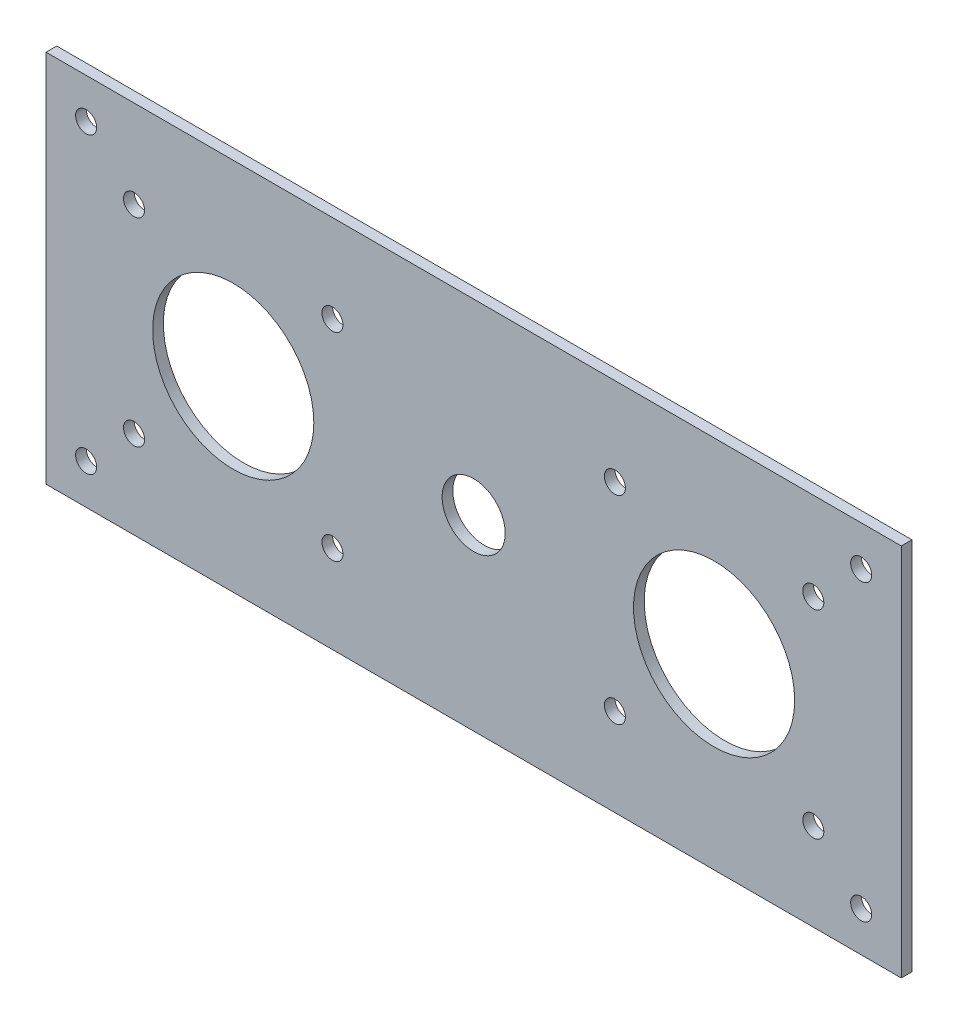
SolidWorks part; units mm, degrees
ref_plane "Front Plane" through (0, 0, 0) normal (0, 0, 1) x (1, 0, 0)
ref_plane "Top Plane" through (0, 0, 0) normal (0, 1, 0) x (1, 0, 0)
ref_plane "Right Plane" through (0, 0, 0) normal (1, 0, 0) x (0, 0, -1)
sketch "Sketch2" plane through (0, 0, 0) normal (0, 0, 1) x (1, 0, 0)
  line L0 (-33.555, 23.57) -> (-80.695, 23.57) construction
  line L1 (-101.6, -44.45) -> (101.6, -44.45)
  line L2 (-101.6, -44.45) -> (-101.6, 44.45)
  line L3 (-101.6, 44.45) -> (101.6, 44.45)
  line L4 (101.6, -44.45) -> (101.6, 44.45)
  line L5 (-101.6, -44.45) -> (101.6, 44.45) construction
  line L6 (-101.6, 44.45) -> (101.6, -44.45) construction
  line L7 (-80.695, 23.57) -> (-80.695, -23.57) construction
  line L8 (-80.695, -23.57) -> (-33.555, -23.57) construction
  line L9 (-33.555, -23.57) -> (-33.555, 23.57) construction
  line L10 (0, 0) -> (57.125, 0) construction
  line L11 (-57.125, 0) -> (-57.125, 23.57) construction
  line L12 (33.555, -23.57) -> (80.695, -23.57) construction
  line L13 (80.695, -23.57) -> (80.695, 23.57) construction
  line L14 (80.695, 23.57) -> (33.555, 23.57) construction
  line L15 (33.555, 23.57) -> (33.555, -23.57) construction
  line L16 (-57.125, 0) -> (-33.555, 0) construction
  line L17 (0, 0) -> (-57.125, 0) construction
  line L18 (57.125, 0) -> (33.555, 0) construction
  line L19 (57.125, 0) -> (57.125, 23.57) construction
  circle A0 centre (-80.695, -23.57) radius 2.5
  circle A1 centre (-33.555, -23.57) radius 2.5
  circle A2 centre (-33.555, 23.57) radius 2.5
  circle A3 centre (-80.695, 23.57) radius 2.5
  circle A4 centre (33.555, 23.57) radius 2.5
  circle A5 centre (80.695, 23.57) radius 2.5
  circle A7 centre (33.555, -23.57) radius 2.5
  circle A8 centre (80.695, -23.57) radius 2.5
  circle A9 centre (-57.125, 0) radius 19.15
  circle A10 centre (57.125, 0) radius 19.15
  point P0 (0, 0)
  dimension "D3" = 5
  dimension "D6" = 38.3
  dimension "D1" = 47.14
  dimension "D2" = 88.9
  dimension "D4" = 203.2
  dimension "D5" = 57.125
extrude "Boss-Extrude1" add sketch "Sketch2" along normal mid plane 2.54
sketch "Sketch3" plane through (0, 0, 1.27) normal (0, 0, 1) x (1, 0, 0)
  line L0 (-101.6, 34.925) -> (-92.075, 34.925) construction
  line L1 (-101.6, 44.45) -> (-101.6, -44.45) construction
  line L2 (-92.075, 34.925) -> (-92.075, 44.45) construction
  line L3 (101.6, 44.45) -> (-101.6, 44.45) construction
  line L4 (92.075, 44.45) -> (92.075, 34.925) construction
  line L5 (92.075, 34.925) -> (101.6, 34.925) construction
  line L6 (101.6, -44.45) -> (101.6, 44.45) construction
  line L7 (92.075, -44.45) -> (92.075, -34.925) construction
  line L8 (-101.6, -44.45) -> (101.6, -44.45) construction
  line L9 (92.075, -34.925) -> (101.6, -34.925) construction
  line L10 (-92.075, -44.45) -> (-92.075, -34.925) construction
  line L11 (-92.075, -34.925) -> (-101.6, -34.925) construction
  circle A0 centre (-92.075, 34.925) radius 2.5
  circle A1 centre (-92.075, -34.925) radius 2.5
  circle A2 centre (92.075, -34.925) radius 2.5
  circle A3 centre (92.075, 34.925) radius 2.5
  dimension "D2" = 5
  dimension "D1" = 9.525
extrude "Cut-Extrude1" cut sketch "Sketch3" against normal through all
sketch "Sketch4" plane through (0, 0, 1.27) normal (0, 0, 1) x (1, 0, 0)
  circle A0 centre (0, 0) radius 7.5
  dimension "D1" = 15
extrude "Cut-Extrude2" cut sketch "Sketch4" against normal through all both and the other way through all
sketch "Sketch5" plane through (0, 0, 1.27) normal (0, 0, 1) x (1, 0, 0)
  line L0 (-85.695, 23.57) -> (-75.695, 23.57) construction
  line L1 (-85.695, 26.07) -> (-75.695, 26.07)
  line L2 (-85.695, 21.07) -> (-75.695, 21.07)
  line L3 (-38.555, 23.57) -> (-28.555, 23.57) construction
  line L4 (-38.555, 26.07) -> (-28.555, 26.07)
  line L5 (-38.555, 21.07) -> (-28.555, 21.07)
  line L6 (-38.555, -23.57) -> (-28.555, -23.57) construction
  line L7 (-38.555, -21.07) -> (-28.555, -21.07)
  line L8 (-38.555, -26.07) -> (-28.555, -26.07)
  line L9 (-75.695, -23.57) -> (-85.695, -23.57) construction
  line L10 (-75.695, -26.07) -> (-85.695, -26.07)
  line L11 (-75.695, -21.07) -> (-85.695, -21.07)
  line L12 (28.555, -23.57) -> (38.555, -23.57) construction
  line L13 (28.555, -21.07) -> (38.555, -21.07)
  line L14 (28.555, -26.07) -> (38.555, -26.07)
  line L15 (75.695, -23.57) -> (85.695, -23.57) construction
  line L16 (75.695, -21.07) -> (85.695, -21.07)
  line L17 (75.695, -26.07) -> (85.695, -26.07)
  line L18 (75.695, 23.57) -> (85.695, 23.57) construction
  line L19 (75.695, 26.07) -> (85.695, 26.07)
  line L20 (75.695, 21.07) -> (85.695, 21.07)
  line L21 (28.555, 23.57) -> (38.555, 23.57) construction
  line L22 (28.555, 26.07) -> (38.555, 26.07)
  line L23 (28.555, 21.07) -> (38.555, 21.07)
  line L24 (76.275, 0) -> (37.975, 0) construction
  line L25 (76.275, -19.15) -> (37.975, -19.15)
  line L26 (76.275, 19.15) -> (37.975, 19.15)
  line L27 (-37.975, 0) -> (-76.275, 0) construction
  line L28 (-37.975, -19.15) -> (-76.275, -19.15)
  line L29 (-37.975, 19.15) -> (-76.275, 19.15)
  line L30 (76.275, -19.15) -> (76.275, 19.15) construction
  line L31 (-76.275, -19.15) -> (-76.275, 19.15) construction
  arc A0 (-85.695, 26.07) -> (-85.695, 21.07) centre (-85.695, 23.57) ccw
  arc A1 (-75.695, 21.07) -> (-75.695, 26.07) centre (-75.695, 23.57) ccw
  arc A2 (-38.555, 26.07) -> (-38.555, 21.07) centre (-38.555, 23.57) ccw
  arc A3 (-28.555, 21.07) -> (-28.555, 26.07) centre (-28.555, 23.57) ccw
  arc A4 (-38.555, -21.07) -> (-38.555, -26.07) centre (-38.555, -23.57) ccw
  arc A5 (-28.555, -26.07) -> (-28.555, -21.07) centre (-28.555, -23.57) ccw
  arc A6 (-75.695, -26.07) -> (-75.695, -21.07) centre (-75.695, -23.57) ccw
  arc A7 (-85.695, -21.07) -> (-85.695, -26.07) centre (-85.695, -23.57) ccw
  arc A8 (28.555, -21.07) -> (28.555, -26.07) centre (28.555, -23.57) ccw
  arc A9 (38.555, -26.07) -> (38.555, -21.07) centre (38.555, -23.57) ccw
  arc A10 (75.695, -21.07) -> (75.695, -26.07) centre (75.695, -23.57) ccw
  arc A11 (85.695, -26.07) -> (85.695, -21.07) centre (85.695, -23.57) ccw
  arc A12 (75.695, 26.07) -> (75.695, 21.07) centre (75.695, 23.57) ccw
  arc A13 (85.695, 21.07) -> (85.695, 26.07) centre (85.695, 23.57) ccw
  arc A14 (28.555, 26.07) -> (28.555, 21.07) centre (28.555, 23.57) ccw
  arc A15 (38.555, 21.07) -> (38.555, 26.07) centre (38.555, 23.57) ccw
  circle A16 centre (57.125, 0) radius 19.15 construction
  arc A17 (76.275, -19.15) -> (76.275, 19.15) centre (76.275, 0) ccw
  arc A18 (37.975, 19.15) -> (37.975, -19.15) centre (37.975, 0) ccw
  circle A19 centre (-57.125, 0) radius 19.15 construction
  arc A20 (-37.975, -19.15) -> (-37.975, 19.15) centre (-37.975, 0) ccw
  arc A21 (-76.275, 19.15) -> (-76.275, -19.15) centre (-76.275, 0) ccw
  point P2 (-80.695, 23.57)
  point P9 (-33.555, 23.57)
  point P17 (-33.555, -23.57)
  point P25 (-80.695, -23.57)
  point P33 (33.555, -23.57)
  point P41 (80.695, -23.57)
  point P49 (80.695, 23.57)
  point P57 (33.555, 23.57)
  point P69 (57.125, 0)
  point P79 (-57.125, 0)
  dimension "D6" = 5
  dimension "D1" = 5
  dimension "D2" = 10
  dimension "D3" = 5
  dimension "D4" = 5
  dimension "D5" = 5
  dimension "5" = 5
  dimension "D7" = 5
  dimension "D8" = 5
  dimension "D9" = 38.3
extrude "Slots Cut-Extrude" [suppressed] cut sketch "Sketch5" against normal through all both and the other way through all
